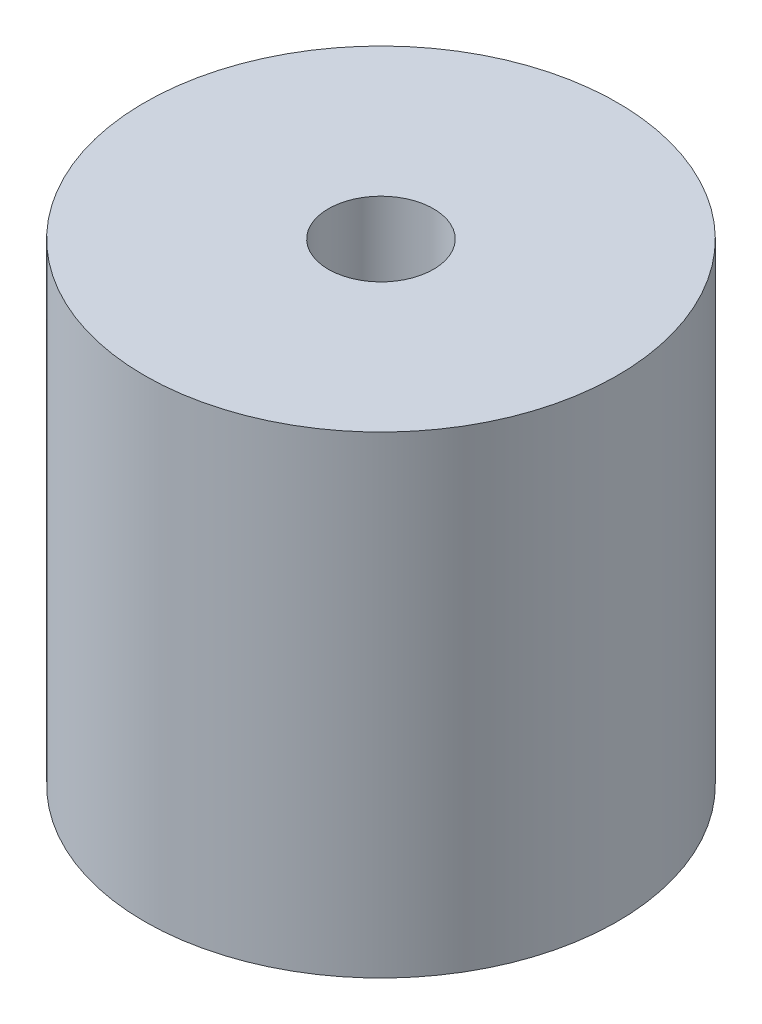
SolidWorks part; units mm, degrees
material "Pure Lead"
ref_plane "Front Plane" through (0, 0, 0) normal (0, 0, 1) x (1, 0, 0)
ref_plane "Top Plane" through (0, 0, 0) normal (0, 1, 0) x (1, 0, 0)
ref_plane "Right Plane" through (0, 0, 0) normal (1, 0, 0) x (0, 0, -1)
sketch "Sketch1" plane through (0, 0, 0) normal (0, 1, 0) x (1, 0, 0)
  circle A0 centre (0, 0) radius 18
  circle A1 centre (0, 0) radius 4
  dimension "D1" = 36
  dimension "D2" = 8
extrude "Boss-Extrude1" add sketch "Sketch1" along normal blind 36
